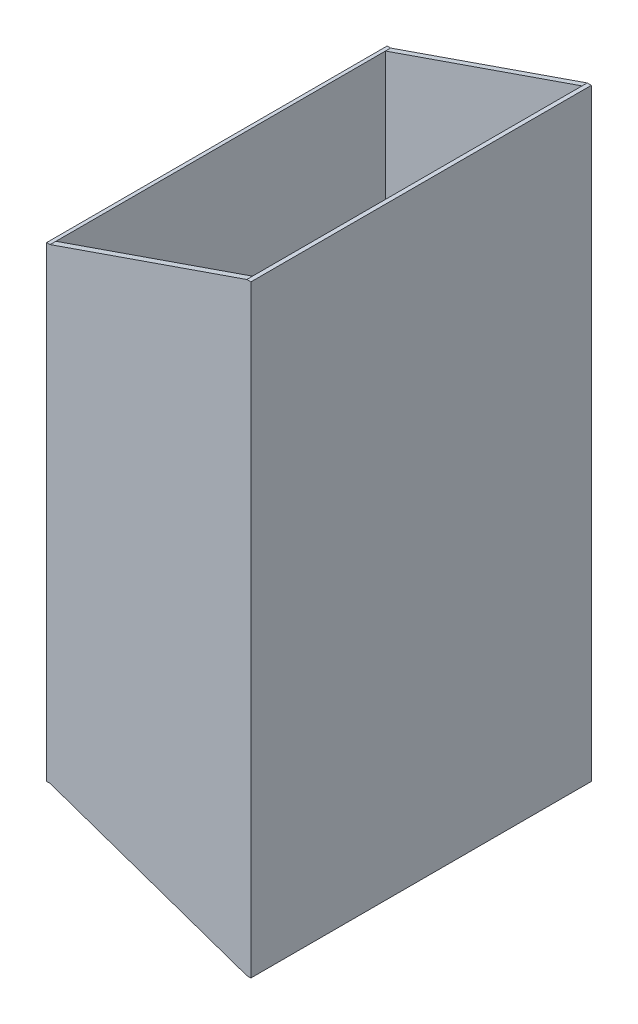
SolidWorks part; units mm, degrees
ref_plane "Front Plane" through (0, 0, 0) normal (0, 0, 1) x (1, 0, 0)
ref_plane "Top Plane" through (0, 0, 0) normal (0, 1, 0) x (1, 0, 0)
ref_plane "Right Plane" through (0, 0, 0) normal (1, 0, 0) x (0, 0, -1)
sketch "Sketch1" plane through (0, 0, 0) normal (0, 0, 1) x (1, 0, 0)
  line L0 (0, 0) -> (0, 44.272)
  line L1 (0, 44.272) -> (15, 44.272)
  line L2 (15, 44.272) -> (15, 0)
  line L3 (15, 0) -> (0, 0)
  line L4 (15, 0) -> (15, 5)
  line L5 (15, 44.272) -> (15, 40.0068)
extrude "Boss-Extrude4" add sketch "Sketch1" along normal blind 25 contours L3 L2 L1 L0
sketch "Sketch4" plane through (0, 44.272, 0) normal (0, 1, 0) x (1, 0, 0)
  line L1 (0.2585, -0.3789) -> (14.6963, -0.3789)
  line L2 (0.2585, -0.3789) -> (0.2585, -24.5793)
  line L3 (0.2585, -24.5793) -> (14.6963, -24.5793)
  line L4 (14.6963, -0.3789) -> (14.6963, -24.5793)
extrude "Cut-Extrude4" cut sketch "Sketch4" against normal through all
sketch "Sketch5" plane through (0, 0, 0) normal (0, 0, -1) x (-1, 0, 0)
  line L0 (-14.6963, 44.272) -> (-0.2585, 44.272)
  line L1 (-0.2585, 44.272) -> (-0.2585, 39.272)
  line L2 (-0.2585, 39.272) -> (-14.6963, 44.272)
extrude "Cut-Extrude5" cut sketch "Sketch5" against normal through all
sketch "Sketch6" plane through (0, 0, 0) normal (0, 0, -1) x (-1, 0, 0)
  line L0 (-0.2585, 0) -> (-0.2585, 5)
  line L1 (-0.2585, 5) -> (-14.6963, 0)
  line L2 (-14.6963, 0) -> (-0.2585, 0)
extrude "Cut-Extrude6" cut sketch "Sketch6" against normal through all
sketch "Sketch7" plane through (0, 0, 0) normal (0, 0, -1) x (-1, 0, 0)
  line L0 (0, 0) -> (0, 44.272) construction
  line L1 (-0.2585, 44.272) -> (0, 44.272)
  line L2 (-0.2585, 44.272) -> (-0.2585, 39.272)
  line L3 (-0.2585, 39.272) -> (0, 39.272)
  line L4 (0, 44.272) -> (0, 39.272)
extrude "Cut-Extrude7" cut sketch "Sketch7" against normal through all
ref_plane "Plane1" through (0.2585, 5, 0) normal (0, 1, 0) x (1, 0, 0)
sketch "Sketch10" plane through (0, 0, 0) normal (0, 0, -1) x (-1, 0, 0)
  line L0 (1.1165, 5) -> (-1.6335, 5) construction
  line L1 (0, 0) -> (-0.2585, 0)
  line L2 (0, 0) -> (0, 5)
  line L3 (0, 5) -> (-0.2585, 5)
  line L4 (-0.2585, 0) -> (-0.2585, 5)
  line L5 (-0.2585, 0) -> (-0.2585, 5) construction
extrude "Cut-Extrude8" cut sketch "Sketch10" against normal through all
